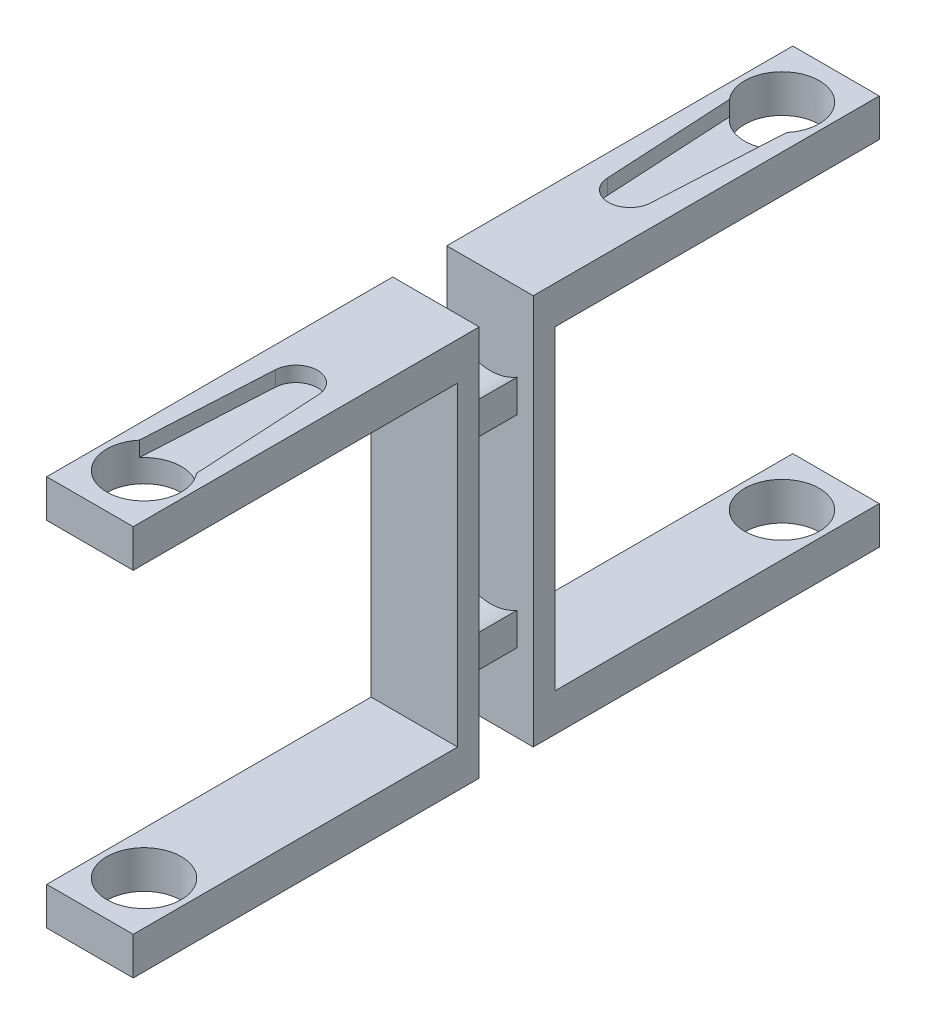
SolidWorks part; units mm, degrees
ref_plane "Front Plane" through (0, 0, 0) normal (0, 0, 1) x (1, 0, 0)
ref_plane "Top Plane" through (0, 0, 0) normal (0, 1, 0) x (1, 0, 0)
ref_plane "Right Plane" through (0, 0, 0) normal (1, 0, 0) x (0, 0, -1)
sketch "Sketch2" plane through (0, 0, 0) normal (0, 0, 1) x (1, 0, 0)
  line L1 (-8.6116, 0.9665) -> (-0.6116, 0.9665)
  line L2 (-8.6116, 0.9665) -> (-8.6116, -35.1835)
  line L3 (-8.6116, -35.1835) -> (-0.6116, -35.1835)
  line L4 (-0.6116, 0.9665) -> (-0.6116, -35.1835)
  dimension "D1" = 8
  dimension "D2" = 36.15
extrude "Boss-Extrude2" add sketch "Sketch2" along normal blind 2
sketch "Sketch11" plane through (0, 0, 2) normal (0, 0, 1) x (1, 0, 0)
  line L0 (-0.6116, 0.9665) -> (-0.6116, -35.1835) construction
  line L1 (-8.6116, 0.9665) -> (-0.6116, 0.9665)
  line L2 (-8.6116, 0.9665) -> (-8.6116, -2.5335)
  line L3 (-8.6116, -2.5335) -> (-0.6116, -2.5335)
  line L4 (-0.6116, 0.9665) -> (-0.6116, -2.5335)
  line L6 (-8.6116, -35.1835) -> (-0.6116, -35.1835)
  line L7 (-8.6116, -35.1835) -> (-8.6116, -31.6835)
  line L8 (-8.6116, -31.6835) -> (-0.6116, -31.6835)
  line L9 (-0.6116, -35.1835) -> (-0.6116, -31.6835)
  dimension "D1" = 3.5
  dimension "D2" = 3.5
extrude "Boss-Extrude8" add sketch "Sketch11" along normal blind 30
sketch "Sketch12" plane through (0, 0.9665, 0) normal (0, 1, 0) x (1, 0, 0)
  line L2 (-2.6146, -12.8409) -> (-1.9616, -24.7909)
  line L6 (-7.2616, -24.7909) -> (-6.6086, -12.8409)
  line L7 (-0.6116, -32) -> (-8.6116, -32) construction
  line L8 (-4.6116, -27) -> (-4.6116, -32) construction
  arc A4 (-7.2616, -24.7909) -> (-1.9616, -24.7909) centre (-4.6116, -27) ccw
  arc A5 (-2.6146, -12.8409) -> (-6.6086, -12.8409) centre (-4.6116, -12.95) ccw
  dimension "D1" = 3.45
  dimension "D5" = 2
  dimension "D2" = 5
  dimension "D3" = 11.95
  dimension "D4" = 11.95
  dimension "D6" = 5.3
extrude "Cut-Extrude1" cut sketch "Sketch12" against normal blind 1.4
sketch "Sketch14" plane through (0, 0, 0) normal (0, 0, -1) x (-1, 0, 0)
  line L0 (2.1116, -6.3119) -> (2.1116, -9.3119)
  line L1 (7.1116, -6.2549) -> (7.1116, -9.2549)
  line L2 (8.6116, 0.9665) -> (0.6116, 0.9665) construction
  line L3 (0.6116, 0.9665) -> (0.6116, -35.1835) construction
  line L4 (2.1116, -24.9825) -> (2.1116, -27.9825)
  line L5 (7.1116, -24.8897) -> (7.1116, -27.8897)
  line L7 (8.6116, 0.9665) -> (8.6116, -35.1835) construction
  line L8 (8.6116, -35.1835) -> (0.6116, -35.1835) construction
  spline S0 degree 2 poles (2.1116, -6.3119) (4.6282, -7.7835) (7.1116, -6.2549) knots 0 0 0 1 1 1
  spline S1 degree 2 poles (2.1116, -9.3119) (4.5927, -7.7833) (7.1116, -9.2549) knots 0 0 0 1 1 1
  spline S2 degree 2 poles (2.1116, -24.9825) (4.6641, -26.4403) (7.1116, -24.8897) knots 0 0 0 1 1 1
  spline S3 degree 2 poles (2.1116, -27.9825) (4.6104, -26.431) (7.1116, -27.8897) knots 0 0 0 1 1 1
  dimension "D1" = 1.5
  dimension "D2" = 3
  dimension "D3" = 8
  dimension "D4" = 1.5
  dimension "D5" = 1.5
  dimension "D6" = 3
  dimension "D7" = 1.5
  dimension "D8" = 1.5
  dimension "D9" = 1.5
  dimension "D10" = 8
extrude "Boss-Extrude9" add sketch "Sketch14" along normal blind 5
sketch "Sketch15" plane through (0, 0, -5) normal (0, 0, -1) x (-1, 0, 0)
  line L1 (0.6116, 0.9665) -> (8.6116, 0.9665)
  line L2 (0.6116, 0.9665) -> (0.6116, -35.1835)
  line L3 (0.6116, -35.1835) -> (8.6116, -35.1835)
  line L4 (8.6116, 0.9665) -> (8.6116, -35.1835)
extrude "Boss-Extrude10" add sketch "Sketch15" along normal blind 2
sketch "Sketch16" plane through (0, 0, -7) normal (0, 0, -1) x (-1, 0, 0)
  line L0 (8.6116, -35.1835) -> (8.6116, 0.9665) construction
  line L1 (0.6116, 0.9665) -> (8.6116, 0.9665)
  line L2 (0.6116, 0.9665) -> (0.6116, -2.5335)
  line L3 (0.6116, -2.5335) -> (8.6116, -2.5335)
  line L4 (8.6116, 0.9665) -> (8.6116, -2.5335)
  line L6 (0.6116, -35.1835) -> (8.6116, -35.1835)
  line L7 (0.6116, -35.1835) -> (0.6116, -31.6835)
  line L8 (0.6116, -31.6835) -> (8.6116, -31.6835)
  line L9 (8.6116, -35.1835) -> (8.6116, -31.6835)
  dimension "D1" = 3.5
  dimension "D2" = 3.5
extrude "Boss-Extrude11" add sketch "Sketch16" along normal blind 30
sketch "Sketch20" plane through (0, 0.9665, 0) normal (0, 1, 0) x (1, 0, 0)
  line L4 (-6.6086, 17.8409) -> (-7.2616, 29.7909)
  line L8 (-1.9616, 29.7909) -> (-2.6146, 17.8409)
  line L9 (-8.6116, 37) -> (-0.6116, 37) construction
  line L10 (-4.6116, 32) -> (-4.6116, 37) construction
  arc A6 (-1.9616, 29.7909) -> (-7.2616, 29.7909) centre (-4.6116, 32) ccw
  arc A7 (-6.6086, 17.8409) -> (-2.6146, 17.8409) centre (-4.6116, 17.95) ccw
  dimension "D1" = 3.45
  dimension "D5" = 2
  dimension "D2" = 5
  dimension "D3" = 11.95
  dimension "D4" = 11.95
  dimension "D6" = 5.3
extrude "Cut-Extrude4" cut sketch "Sketch20" against normal blind 1.4
sketch "Sketch22" plane through (0, 0.9665, 0) normal (0, 1, 0) x (1, 0, 0)
  circle A0 centre (-4.6116, -27) radius 3.45
  dimension "D1" = 6.9
extrude "Cut-Extrude6" cut sketch "Sketch22" against normal through all
sketch "Sketch23" plane through (0, 0.9665, 0) normal (0, 1, 0) x (1, 0, 0)
  circle A0 centre (-4.6116, 32) radius 3.45
  dimension "D1" = 6.9
extrude "Cut-Extrude7" cut sketch "Sketch23" against normal through all
